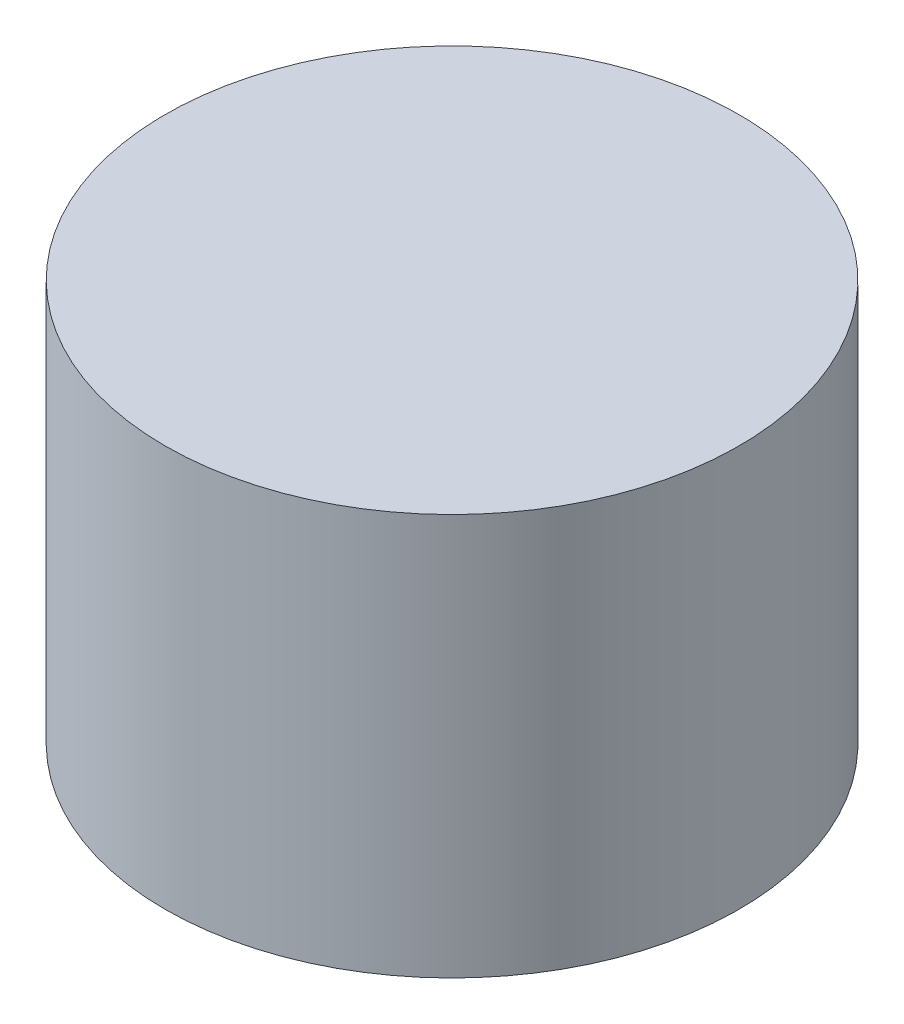
SolidWorks part; units mm, degrees
material "Rubber"
ref_plane "Front Plane" through (0, 0, 0) normal (0, 0, 1) x (1, 0, 0)
ref_plane "Top Plane" through (0, 0, 0) normal (0, 1, 0) x (1, 0, 0)
ref_plane "Right Plane" through (0, 0, 0) normal (1, 0, 0) x (0, 0, -1)
sketch "Sketch2" plane through (0, 0, 0) normal (0, 1, 0) x (1, 0, 0)
  circle A0 centre (0, 0) radius 7.15
extrude "Boss-Extrude1" add sketch "Sketch2" along normal blind 10
